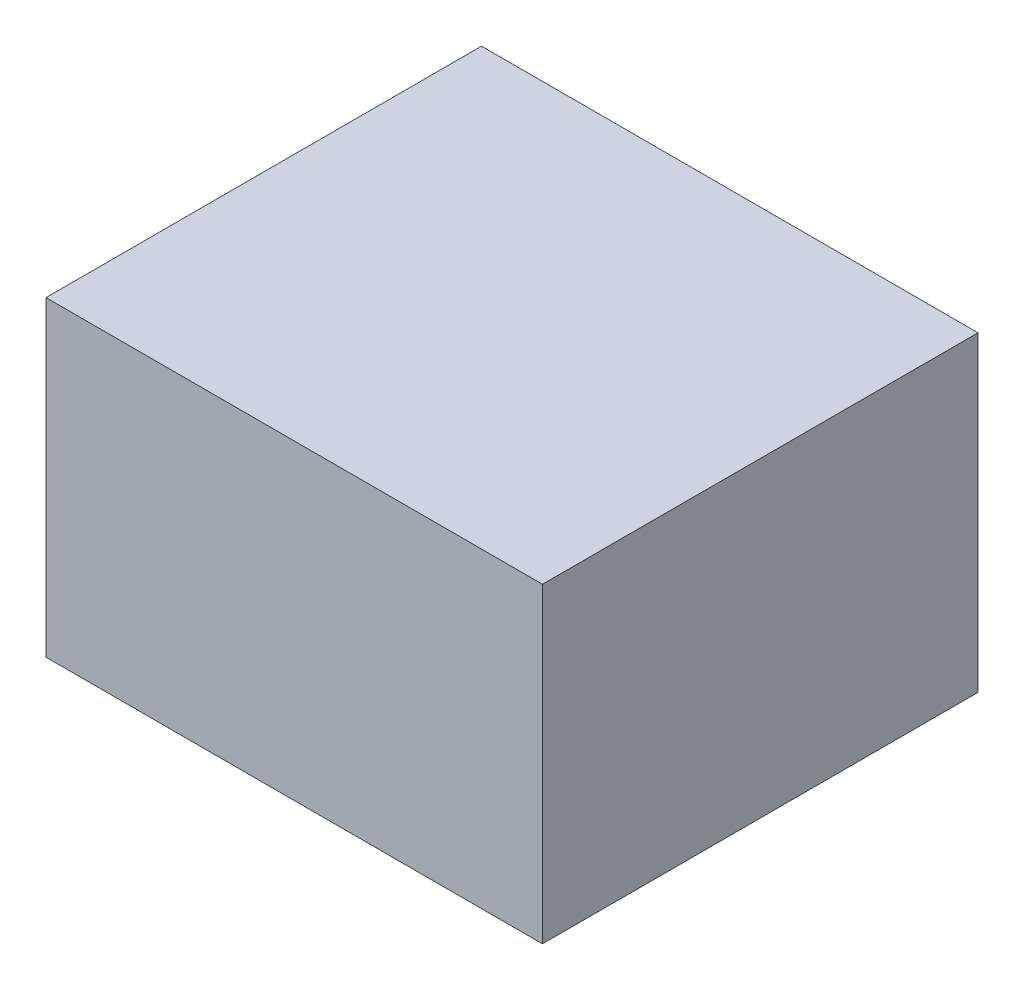
SolidWorks part; units mm, degrees
ref_plane "Front Plane" through (0, 0, 0) normal (0, 0, 1) x (1, 0, 0)
ref_plane "Top Plane" through (0, 0, 0) normal (0, 1, 0) x (1, 0, 0)
ref_plane "Right Plane" through (0, 0, 0) normal (1, 0, 0) x (0, 0, -1)
sketch "Sketch1" plane through (0, 0, 0) normal (0, 1, 0) x (1, 0, 0)
  line L1 (-30.6643, 15.9657) -> (25.2157, 15.9657)
  line L2 (-30.6643, 15.9657) -> (-30.6643, -33.0563)
  line L3 (-30.6643, -33.0563) -> (25.2157, -33.0563)
  line L4 (25.2157, 15.9657) -> (25.2157, -33.0563)
  line L5 (-2.7243, -33.0563) -> (-2.7243, 15.9657) construction
  line L6 (-30.6643, -8.5453) -> (25.2157, -8.5453) construction
  point P268 (-2.7243, -8.5453)
  dimension "D1" = 55.88
  dimension "D2" = 49.022
extrude "Boss-Extrude1" add sketch "Sketch1" along normal blind 35.052
sketch "Sketch2" plane through (0, 0, -15.9657) normal (0, 0, -1) x (-1, 0, 0)
  line L0 (-25.2157, 35.052) -> (-25.2157, 0) construction
  circle A0 centre (-15.0557, 17.526) radius 3.175
  dimension "D1" = 6.35
  dimension "D2" = 10.16
extrude "Boss-Extrude2" add sketch "Sketch2" along normal blind 5.08
sketch "Sketch3" plane through (-30.6643, 0, 0) normal (-1, 0, 0) x (0, 0, 1)
  line L0 (-15.9657, 17.526) -> (33.0563, 17.526) construction
  line L1 (-15.9657, 35.052) -> (-15.9657, 0) construction
  line L2 (33.0563, 35.052) -> (33.0563, 0) construction
